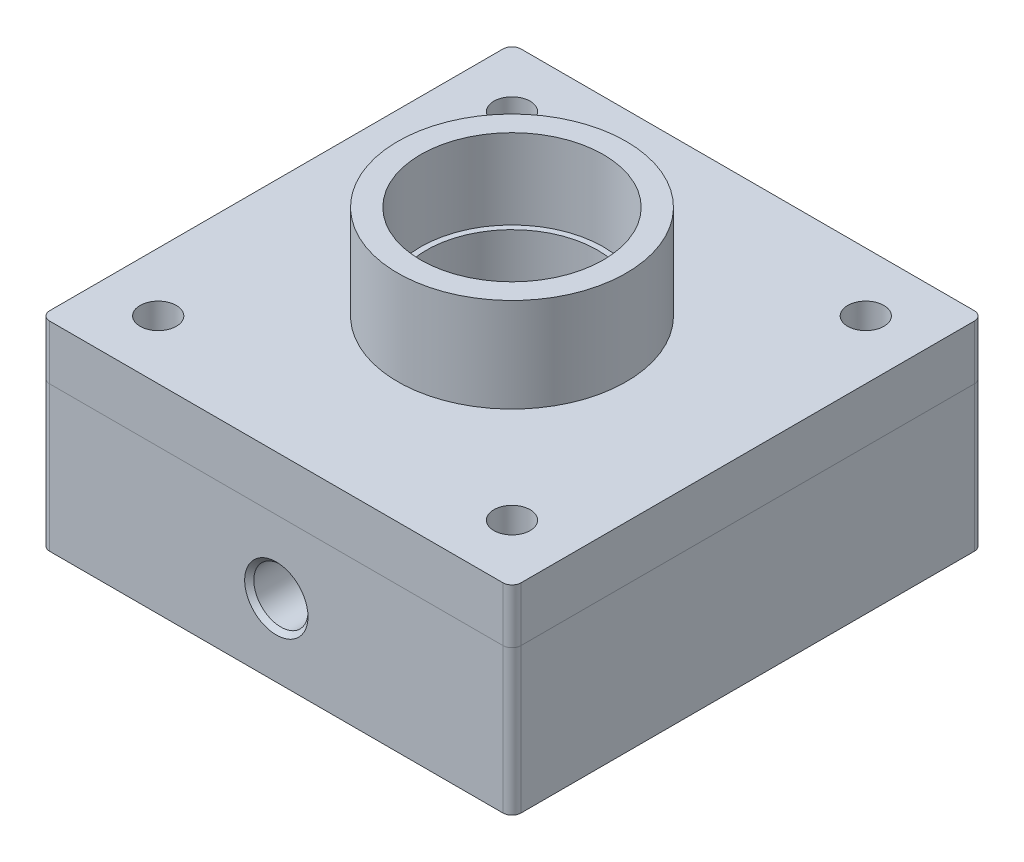
SolidWorks part; units mm, degrees
ref_plane "Front Plane" through (0, 0, 0) normal (0, 0, 1) x (1, 0, 0)
ref_plane "Top Plane" through (0, 0, 0) normal (0, 1, 0) x (1, 0, 0)
ref_plane "Right Plane" through (0, 0, 0) normal (1, 0, 0) x (0, 0, -1)
sketch "Sketch1" plane through (0, 0, 0) normal (0, 1, 0) x (1, 0, 0)
  line L1 (82.55, -82.55) -> (-82.55, -82.55)
  line L2 (82.55, -82.55) -> (82.55, 82.55)
  line L3 (82.55, 82.55) -> (-82.55, 82.55)
  line L4 (-82.55, -82.55) -> (-82.55, 82.55)
  line L5 (82.55, -82.55) -> (-82.55, 82.55) construction
  line L6 (82.55, 82.55) -> (-82.55, -82.55) construction
  point P0 (0, 0)
  dimension "D1" = 165.1
extrude "Boss-Extrude1" add sketch "Sketch1" along normal blind 50.8
sketch "Sketch2" plane through (0, 50.8, 0) normal (0, 1, 0) x (1, 0, 0)
  circle A0 centre (0, 0) radius 40
  dimension "D1" = 80
extrude "Boss-Extrude2" add sketch "Sketch2" along normal blind 52
sketch "Sketch3" plane through (0, 102.8, 0) normal (0, 1, 0) x (1, 0, 0)
  circle A0 centre (0, 0) radius 32
  dimension "D1" = 64
extrude "Cut-Extrude1" cut sketch "Sketch3" against normal blind 28
sketch "Sketch4" plane through (0, 74.8, 0) normal (0, 1, 0) x (1, 0, 0)
  circle A0 centre (0, 0) radius 30
  dimension "D1" = 60
extrude "Cut-Extrude2" cut sketch "Sketch4" against normal blind 22
fillet "Fillet1" radius 3.175 4 edges at (-82.55, 25.4, -82.55) (82.55, 25.4, -82.55) (-82.55, 25.4, 82.55) (82.55, 25.4, 82.55)
sketch "Sketch5" plane through (0, 0, 0) normal (0, -1, 0) x (1, 0, 0)
  circle A0 centre (0, 0) radius 20
  dimension "D1" = 40
extrude "Cut-Extrude3" cut sketch "Sketch5" against normal blind 40
sketch "Sketch6" plane through (0, 0, 0) normal (0, -1, 0) x (1, 0, 0)
  circle A0 centre (0, 0) radius 76.2
  circle A1 centre (0, 0) radius 69.85
  dimension "D1" = 152.4
  dimension "D2" = 139.7
extrude "Cut-Extrude4" cut sketch "Sketch6" against normal blind 8
sketch "Sketch7" plane through (0, 0, 82.55) normal (0, 0, 1) x (1, 0, 0)
  line L0 (-79.375, 25.4) -> (79.375, 25.4) construction
  line L1 (-79.375, 50.8) -> (-79.375, 0) construction
  line L2 (79.375, 0) -> (79.375, 50.8) construction
hole_wizard "1/2-14 NPSM Tapped Hole1" positions "Sketch8" profile "Sketch9" tap size "1/2-14 NPSM" standard "ANSI Inch"
sketch "Sketch8" plane through (0, 0, 82.55) normal (0, 0, 1) x (1, 0, 0)
  line L0 (-79.375, 25.4) -> (79.375, 25.4) construction
  point P0 (0, 25.4)
sketch "Sketch9" plane through (0, 25.4, 82.55) normal (1, 0, 0) x (0, -1, 0)
  line L0 (0, 0) -> (0, 52.9403)
  line L1 (0, 52.9403) -> (9.4869, 47.24)
  line L2 (9.4869, 47.24) -> (9.4869, 1.6002)
  line L3 (9.4869, 1.6002) -> (11.0871, 0)
  line L5 (11.0871, 0) -> (0, 0)
  line L6 (-9.4869, 1.6002) -> (-11.0871, 0) construction
  line L10 (0, 52.9403) -> (-9.4869, 47.24) construction
  line L11 (0, -6.35) -> (0, 107.95) construction
  dimension "Tap Drill Dia." = 18.9738
  dimension "Tap Drill Depth" = 47.24
  dimension "Near C'Sink Dia." = 22.1742
  dimension "Near C'Sink Angle" = 90
  dimension "Drill Angle" = 118
cosmetic thread "Hole Thread1" parameters "D1"=41.91, "D2"=20.9042
sketch "Sketch10" plane through (0, 0, 0) normal (0, -1, 0) x (1, 0, 0)
  line L0 (-79.375, 82.55) -> (79.375, 82.55) construction
  circle A0 centre (0, 50.55) radius 6.35
  dimension "D2" = 12.7
  dimension "D1" = 32
extrude "Cut-Extrude5" cut sketch "Sketch10" against normal blind 25
sketch "Sketch11" plane through (0, 0, 0) normal (0, -1, 0) x (1, 0, 0)
  line L1 (61.9638, -61.9638) -> (-61.9638, -61.9638) construction
  line L2 (61.9638, -61.9638) -> (61.9638, 61.9638) construction
  line L3 (61.9638, 61.9638) -> (-61.9638, 61.9638) construction
  line L4 (-61.9638, -61.9638) -> (-61.9638, 61.9638) construction
  line L5 (61.9638, -61.9638) -> (-61.9638, 61.9638) construction
  line L6 (61.9638, 61.9638) -> (-61.9638, -61.9638) construction
  circle A0 centre (0, 0) radius 87.63 construction
  circle A1 centre (-61.9638, 61.9638) radius 6.35
  circle A2 centre (61.9638, 61.9638) radius 6.35
  circle A3 centre (61.9638, -61.9638) radius 6.35
  circle A4 centre (-61.9638, -61.9638) radius 6.35
  dimension "D1" = 175.26
  dimension "D2" = 12.7
extrude "Cut-Extrude6" cut sketch "Sketch11" against normal through all
sketch "Sketch12" plane through (0, 50.8, 0) normal (0, 1, 0) x (1, 0, 0)
  line L4 (79.375, 82.55) -> (-79.375, 82.55)
  line L5 (-82.55, 79.375) -> (-82.55, -79.375)
  line L6 (-79.375, -82.55) -> (79.375, -82.55)
  line L7 (82.55, -79.375) -> (82.55, 79.375)
  line L8 (79.375, 82.55) -> (-79.375, 82.55)
  line L9 (-82.55, 79.375) -> (-82.55, -79.375)
  line L10 (-79.375, -82.55) -> (79.375, -82.55)
  line L11 (82.55, -79.375) -> (82.55, 79.375)
  circle A0 centre (-61.9638, 61.9638) radius 6.35 construction
  circle A1 centre (61.9638, 61.9638) radius 6.35 construction
  circle A2 centre (0, 0) radius 40 construction
  circle A3 centre (61.9638, -61.9638) radius 6.35 construction
  arc A4 (-79.375, 82.55) -> (-82.55, 79.375) centre (-79.375, 79.375) ccw
  arc A5 (-82.55, -79.375) -> (-79.375, -82.55) centre (-79.375, -79.375) ccw
  arc A6 (79.375, -82.55) -> (82.55, -79.375) centre (79.375, -79.375) ccw
  arc A7 (82.55, 79.375) -> (79.375, 82.55) centre (79.375, 79.375) ccw
  arc A8 (-79.375, 82.55) -> (-82.55, 79.375) centre (-79.375, 79.375) ccw
  arc A9 (-82.55, -79.375) -> (-79.375, -82.55) centre (-79.375, -79.375) ccw
  arc A10 (79.375, -82.55) -> (82.55, -79.375) centre (79.375, -79.375) ccw
  arc A11 (82.55, 79.375) -> (79.375, 82.55) centre (79.375, 79.375) ccw
  circle A12 centre (-61.9638, -61.9638) radius 6.35 construction
  circle A13 centre (-61.9638, 61.9638) radius 6.35
  circle A14 centre (61.9638, 61.9638) radius 6.35
  circle A15 centre (0, 0) radius 40
  circle A16 centre (61.9638, -61.9638) radius 6.35
  circle A17 centre (-61.9638, -61.9638) radius 6.35
  dimension "D1" = 0
extrude "Boss-Extrude3" add sketch "Sketch12" along normal blind 19.05 separate body
